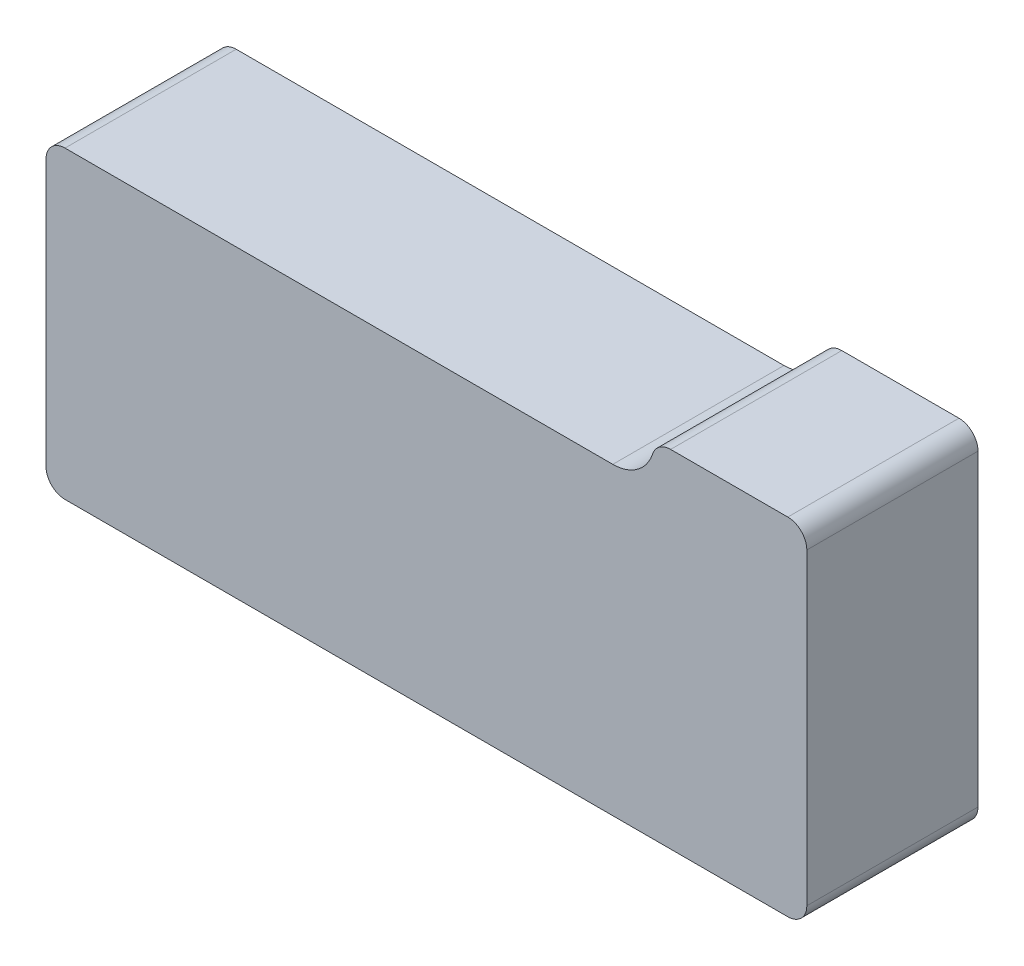
SolidWorks part; units mm, degrees
ref_plane "Plane1" through (0, 0, 0) normal (0, 0, 1) x (1, 0, 0)
ref_plane "Plane2" through (0, 0, 0) normal (0, 1, 0) x (1, 0, 0)
ref_plane "Plane3" through (0, 0, 0) normal (1, 0, 0) x (0, 0, -1)
sketch "Sketch1" plane through (0, 0, 0) normal (0, 0, 1) x (1, 0, 0)
  line L0 (100, 0) -> (-100, 0) construction
  line L1 (-95, 40) -> (49, 40)
  line L2 (-100, 35) -> (-100, -35)
  line L3 (-95, -40) -> (95, -40)
  line L4 (100, 46) -> (100, -35)
  line L5 (95, 51) -> (64.1987, 51)
  line L6 (0, 0) -> (0, 15.7241) construction
  arc A0 (-95, 40) -> (-100, 35) centre (-95, 35) ccw
  arc A1 (-100, -35) -> (-95, -40) centre (-95, -35) ccw
  arc A2 (95, -40) -> (100, -35) centre (95, -35) ccw
  arc A3 (59.4491, 47.5625) -> (64.1987, 51) centre (64.1987, 46) cw
  arc A4 (49, 40) -> (59.4491, 47.5625) centre (49, 51) ccw
  arc A5 (100, 46) -> (95, 51) centre (95, 46) ccw
  point P21 (60, 51)
  dimension "D1" = 5
  dimension "D5" = 40
  dimension "D6" = 11
  dimension "D7" = 5
  dimension "D8" = 5
  dimension "D2" = 200
  dimension "D3" = 11
  dimension "D4" = 80
extrude "Extrude1" add sketch "Sketch1" along normal blind 45
sketch "CenterLine" plane through (91.2746, -269.023, 0) normal (0, 0, -1) x (-1, 0, 0)
  line L0 (16.7805, 334.023) -> (16.7805, 314.023)
  line L1 (-1.2195, 334.023) -> (-1.2195, 257.523)
  line L4 (162.735, 299.023) -> (162.735, 239.023) construction
  line L5 (17.2805, 299.023) -> (17.2805, 239.023) construction
  line L8 (-8.7254, 269.023) -> (191.2746, 269.023) construction
  line L9 (31.7805, 299.023) -> (162.735, 299.023)
  line L10 (162.735, 239.023) -> (17.2805, 239.023)
  line L11 (181.235, 280.523) -> (181.235, 257.523)
  line L13 (17.2805, 269.023) -> (162.735, 269.023) construction
  line L14 (42.2746, 309.023) -> (186.2746, 309.023) construction
  arc A4 (162.735, 299.023) -> (181.235, 280.523) centre (162.735, 280.523) cw
  arc A5 (-1.2195, 257.523) -> (17.2805, 239.023) centre (17.2805, 257.523) ccw
  arc A7 (162.735, 239.023) -> (181.235, 257.523) centre (162.735, 257.523) ccw
  arc A10 (31.7805, 299.023) -> (16.7805, 314.023) centre (31.7805, 314.023) cw
  point P3 (90.0078, 269.023)
  point P10 (0, 0)
  point P11 (31.7805, 299.023)
  dimension "D3" = 15
  dimension "D6" = 60
  dimension "D9" = 18.5
  dimension "D10" = 35
  dimension "D11" = 18.5
  dimension "D7" = 145.4545
  dimension "D13" = 35
  dimension "D5" = 18
